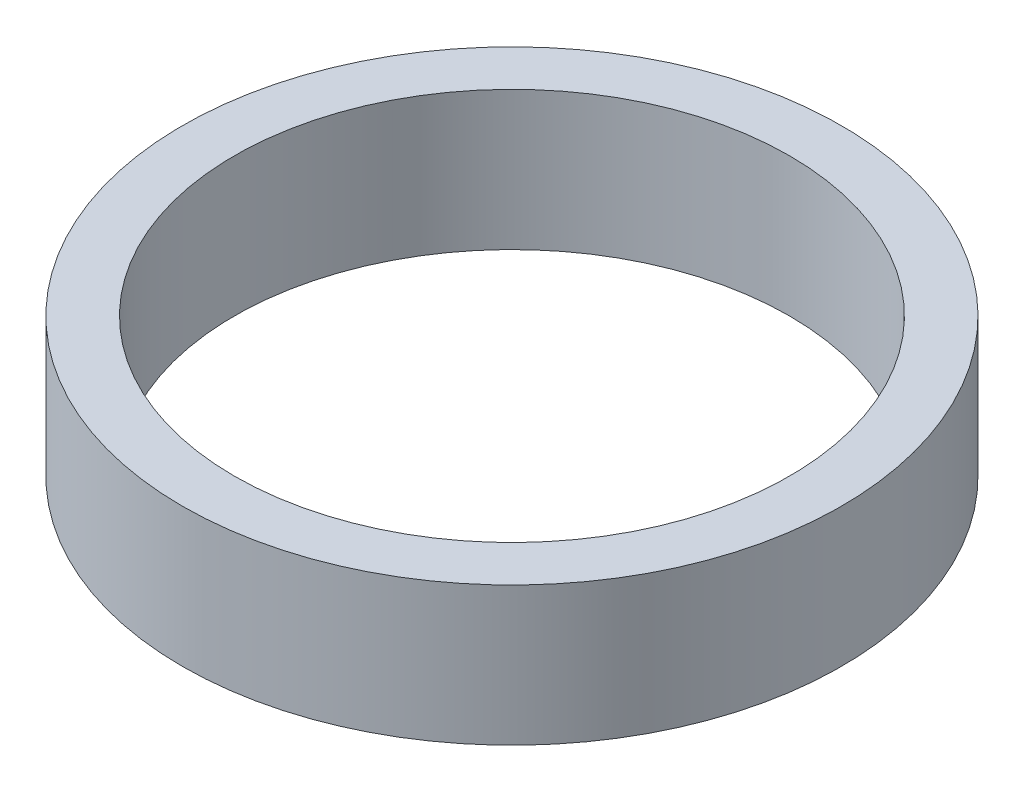
SolidWorks part; units mm, degrees
ref_plane "Front Plane" through (0, 0, 0) normal (0, 0, 1) x (1, 0, 0)
ref_plane "Top Plane" through (0, 0, 0) normal (0, 1, 0) x (1, 0, 0)
ref_plane "Right Plane" through (0, 0, 0) normal (1, 0, 0) x (0, 0, -1)
other "Default"
sketch "Sketch1" plane through (0, 0, 0) normal (0, 1, 0) x (1, 0, 0)
  circle A0 centre (0, 0) radius 25.4
  circle A1 centre (0, 0) radius 30.1625
  dimension "ID" = 50.8
  dimension "OD" = 60.325
extrude "Boss-Extrude1" add sketch "Sketch1" along normal mid plane 12.7
